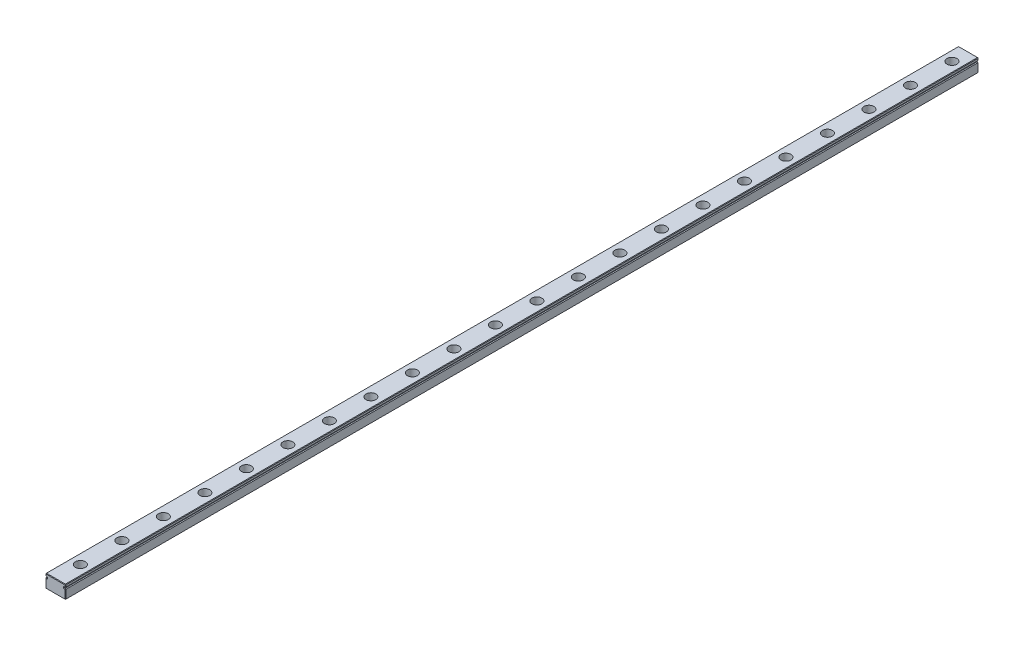
SolidWorks part; units mm, degrees
material "AISI 304"
ref_plane "Front Plane" through (0, 0, 0) normal (0, 0, 1) x (1, 0, 0)
ref_plane "Top Plane" through (0, 0, 0) normal (0, 1, 0) x (1, 0, 0)
ref_plane "Right Plane" through (0, 0, 0) normal (1, 0, 0) x (0, 0, -1)
sketch "Sketch1" plane through (0, 0, 0) normal (0, 0, 1) x (1, 0, 0)
  line L0 (0, 0) -> (0, 8) construction
  line L1 (0, 8) -> (12, 8)
  line L2 (0, 0) -> (12, 0)
  line L3 (0, 8) -> (0, 6.75)
  line L4 (0, 6.75) -> (0.5, 6.25) construction
  line L5 (0.5, 6.25) -> (1, 6.25)
  line L6 (0.5, 5.75) -> (0, 5.25) construction
  line L7 (0, 5.25) -> (0, 0)
  line L8 (1, 6.25) -> (1, 5.75)
  line L9 (1, 5.75) -> (0.5, 5.75)
  line L10 (0.5, 5.75) -> (0.75, 6) construction
  line L11 (0.75, 6) -> (0.5, 6.25) construction
  line L12 (0, 6.75) -> (0, 6.559)
  line L13 (0, 5.25) -> (0, 5.441)
  line L14 (6, 8) -> (6, 0) construction
  line L15 (11.25, 6) -> (11.5, 6.25) construction
  line L16 (11.5, 5.75) -> (11.25, 6) construction
  line L17 (11.5, 5.75) -> (12, 5.25) construction
  line L18 (12, 6.75) -> (11.5, 6.25) construction
  line L19 (12, 0) -> (12, 8) construction
  line L20 (12, 5.25) -> (12, 5.441)
  line L21 (12, 6.75) -> (12, 6.559)
  line L22 (11, 5.75) -> (11.5, 5.75)
  line L23 (11, 6.25) -> (11, 5.75)
  line L24 (12, 5.25) -> (12, 0)
  line L25 (11.5, 6.25) -> (11, 6.25)
  line L26 (12, 8) -> (12, 6.75)
  arc A0 (0, 5.441) -> (0.5, 5.75) centre (0, 6) ccw
  arc A1 (0.5, 6.25) -> (0, 6.559) centre (0, 6) ccw
  arc A2 (11.5, 6.25) -> (12, 6.559) centre (12, 6) cw
  arc A3 (12, 5.441) -> (11.5, 5.75) centre (12, 6) cw
  point P4 (1, 6)
  point P28 (11, 6)
  dimension "D1" = 8
  dimension "D2" = 6
  dimension "D3" = 0.5
  dimension "D4" = 45
  dimension "D5" = 2
  dimension "D6" = 1
extrude "Boss-Extrude1" add sketch "Sketch1" along normal blind 550
chamfer "Chamfer1" distance 0.3 angle 45 36 edges at (0, 0, 275) (12, 0, 275) (0, 8, 275) (12, 8, 275) (0.2939, 5.5245, 550) (0.75, 5.75, 550) (1, 6, 550) (0.75, 6.25, 550) (0.2939, 6.4755, 550) (0, 7.2795, 550) (6, 8, 550) (12, 7.2795, 550) (11.7061, 6.4755, 550) (11.25, 6.25, 550) (11, 6, 550) (11.25, 5.75, 550) (11.7061, 5.5245, 550) (12, 2.7205, 550) (6, 0, 550) (0, 2.7205, 550) (12, 2.7205, 0) (11.7061, 5.5245, 0) (11.25, 5.75, 0) (11, 6, 0) (11.25, 6.25, 0) (11.7061, 6.4755, 0) (12, 7.2795, 0) (6, 0, 0) (0, 2.7205, 0) (0.2939, 5.5245, 0) (0.75, 5.75, 0) (1, 6, 0) (0.75, 6.25, 0) (0.2939, 6.4755, 0) (0, 7.2795, 0) (6, 8, 0)
hole_wizard "Цековка для  болта с шестигранной головкой M51" positions "3DSketch1" profile "Sketch3" counterbore size "M5" standard "Ansi Metric" end condition through all
sketch3d "3DSketch1"
  line L0 (6, 8, 0) -> (6, 8, 10) construction
  line L1 (11.7, 8, 0) -> (0.3, 8, 0) construction
  point P0 (6, 8, 10)
  dimension "D1" = 10
sketch "Sketch3" plane through (6, 8, 10) normal (1, 0, 0) x (0, 0, 1)
  line L0 (0, 0) -> (0, 8)
  line L1 (0, 8) -> (1.75, 8)
  line L3 (1.75, 8) -> (1.75, 4.5)
  line L4 (1.75, 4.5) -> (3, 4.5)
  line L5 (3, 4.5) -> (3, 0)
  line L7 (3, 0) -> (0, 0)
  line L11 (0, -6.35) -> (0, 107.95) construction
  dimension "Диаметр сквозного отверстия" = 3.5
  dimension "Глубина сквозного отверстия" = 8
  dimension "Диаметр цековки" = 6
  dimension "Глубина цековки" = 4.5
pattern_linear "LPattern1" count 22 spacing 25 along (0, 0, 1) of "Цековка для  болта с шестигранной головкой M51"
